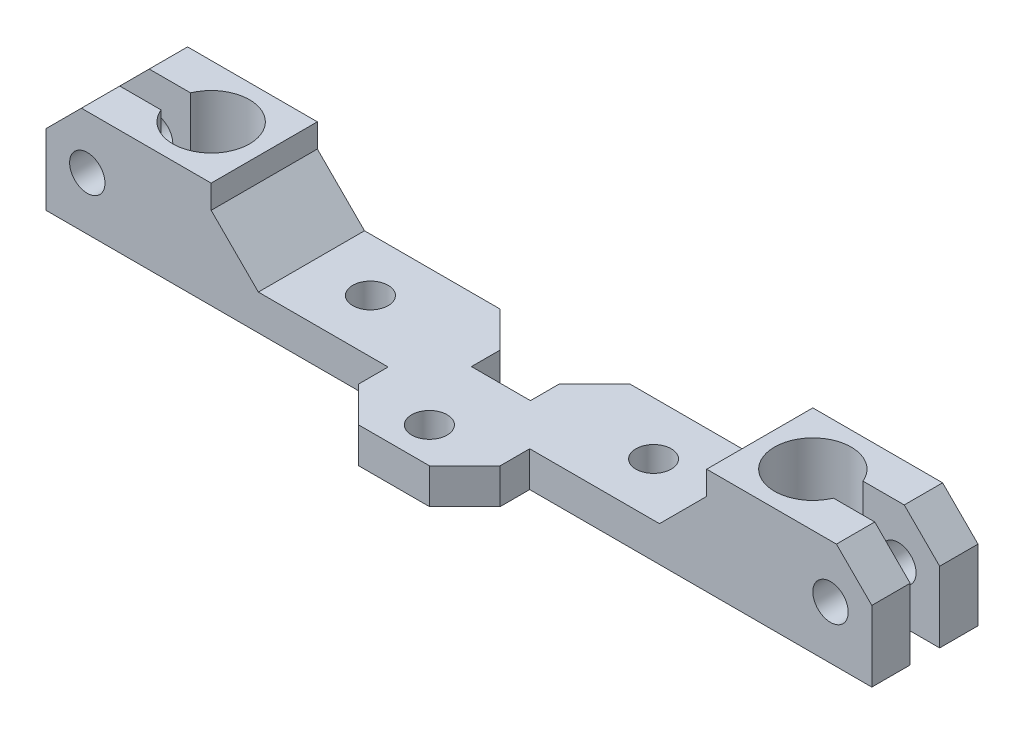
SolidWorks part; units mm, degrees
ref_plane "Plan de face" through (0, 0, 0) normal (0, 0, 1) x (1, 0, 0)
ref_plane "Plan de dessus" through (0, 0, 0) normal (0, 1, 0) x (1, 0, 0)
ref_plane "Plan de droite" through (0, 0, 0) normal (1, 0, 0) x (0, 0, -1)
sketch "Esquisse1" plane through (0, 0, 0) normal (0, 1, 0) x (1, 0, 0)
  line L0 (13.2163, 8.0498) -> (13.2163, -16.4268) construction
  line L1 (-21.7837, 7.99) -> (10.7163, 7.99)
  line L2 (-21.7837, 7.99) -> (-21.7837, -1.01)
  line L3 (-21.7837, -1.01) -> (7.2163, -1.01)
  line L4 (48.2163, 7.99) -> (48.2163, -1.01)
  line L5 (19.2163, -1.01) -> (48.2163, -1.01)
  line L6 (15.7163, 7.99) -> (48.2163, 7.99)
  line L7 (7.2163, -1.01) -> (7.2163, -6.51)
  line L8 (7.2163, -6.51) -> (19.2163, -6.51)
  line L9 (19.2163, -1.01) -> (19.2163, -6.51)
  line L11 (10.7163, 7.99) -> (10.7163, 2.5523)
  line L12 (10.7163, 2.5523) -> (15.7163, 2.5523)
  line L13 (15.7163, 7.99) -> (15.7163, 2.5523)
  dimension "D1" = 70
  dimension "D2" = 9
  dimension "D3" = 6
  dimension "D4" = 6
  dimension "D5" = 2.5
  dimension "D6" = 2.5
  dimension "D7" = 5.5
extrude "Boss.-Extru.1" add sketch "Esquisse1" along normal blind 3
sketch "Esquisse2" plane through (0, 3, 0) normal (0, 1, 0) x (1, 0, 0)
  line L1 (-21.7837, 7.99) -> (-7.7837, 7.99)
  line L2 (-21.7837, 7.99) -> (-21.7837, -1.01)
  line L3 (-21.7837, -1.01) -> (-7.7837, -1.01)
  line L4 (-7.7837, 7.99) -> (-7.7837, -1.01)
  line L5 (13.2163, 7.99) -> (13.2163, -21.6724) construction
  line L6 (48.2163, 7.99) -> (34.2163, 7.99)
  line L7 (48.2163, 7.99) -> (48.2163, -1.01)
  line L8 (48.2163, -1.01) -> (34.2163, -1.01)
  line L9 (34.2163, 7.99) -> (34.2163, -1.01)
  dimension "D1" = 21
  dimension "D2" = 21
extrude "Boss.-Extru.2" add sketch "Esquisse2" along normal blind 6
sketch "Esquisse3" plane through (0, 9, 0) normal (0, 1, 0) x (1, 0, 0)
  line L0 (-7.7837, -1.01) -> (-16.7837, 7.99) construction
  line L1 (-7.7837, 7.99) -> (-21.7837, 7.99) construction
  line L2 (34.2163, -1.01) -> (43.2163, 7.99) construction
  line L3 (48.2163, 7.99) -> (34.2163, 7.99) construction
  line L4 (34.2163, -1.01) -> (48.2163, -1.01) construction
  line L5 (-7.7837, -1.01) -> (-7.7837, 7.99) construction
  line L6 (34.2163, 7.99) -> (34.2163, -1.01) construction
  circle A0 centre (-12.2837, 3.49) radius 3.25
  circle A1 centre (38.7163, 3.49) radius 3.25
  dimension "D1" = 6.5
  dimension "D2" = 6.5
  dimension "D3" = 9
  dimension "D4" = 9
extrude "Enlèv. mat.-Extru.1" cut sketch "Esquisse3" against normal through all
chamfer "Chanfrein1" distance 4 angle 45 2 edges at (34.2163, 3, -3.49)
sketch "Esquisse4" plane through (0, 3, 0) normal (0, 1, 0) x (1, 0, 0)
  line L0 (-3.7837, 3.49) -> (30.2163, 3.49) construction
  line L1 (13.2163, 3.49) -> (13.2163, -6.51) construction
  line L2 (7.2163, -6.51) -> (19.2163, -6.51) construction
  line L3 (-3.7837, 7.99) -> (-3.7837, -1.01) construction
  line L4 (30.2163, -1.01) -> (30.2163, 7.99) construction
  circle A0 centre (1.2163, 3.49) radius 1.5
  circle A1 centre (25.2163, 3.49) radius 1.5
  circle A2 centre (13.2163, -3.51) radius 1.5
  dimension "D1" = 3
  dimension "D2" = 3
  dimension "D5" = 3
  dimension "D3" = 5
  dimension "D4" = 5
  dimension "D7" = 7
extrude "Enlèv. mat.-Extru.2" cut sketch "Esquisse4" against normal through all
sketch "Esquisse5" plane through (0, 9, 0) normal (0, 1, 0) x (1, 0, 0)
  line L0 (-21.7837, 3.49) -> (48.2163, 3.49) construction
  line L1 (-21.7837, 7.99) -> (-21.7837, -1.01) construction
  line L2 (48.2163, -1.01) -> (48.2163, 7.99) construction
  line L4 (-21.7837, 4.74) -> (-12.2837, 4.74)
  line L5 (-21.7837, 4.74) -> (-21.7837, 2.24)
  line L6 (-21.7837, 2.24) -> (-12.2837, 2.24)
  line L7 (-12.2837, 4.74) -> (-12.2837, 2.24)
  line L8 (48.2163, 4.74) -> (38.7163, 4.74)
  line L9 (48.2163, 4.74) -> (48.2163, 2.24)
  line L10 (48.2163, 2.24) -> (38.7163, 2.24)
  line L11 (38.7163, 4.74) -> (38.7163, 2.24)
  circle A0 centre (-12.2837, 3.49) radius 3.25 construction
  circle A1 centre (38.7163, 3.49) radius 3.25 construction
  dimension "D1" = 1.25
  dimension "D2" = 1.25
  dimension "D3" = 1.25
  dimension "D4" = 1.25
  dimension "D5" = 0
  dimension "D6" = 0
extrude "Enlèv. mat.-Extru.3" cut sketch "Esquisse5" against normal through all
sketch "Esquisse6" plane through (0, 0, 1.01) normal (0, 0, 1) x (1, 0, 0)
  line L0 (-21.7837, 9) -> (-14.7837, 0) construction
  line L1 (-21.7837, 0) -> (7.2163, 0) construction
  line L2 (-21.7837, 9) -> (-21.7837, 0) construction
  line L3 (48.2163, 9) -> (41.2163, 0) construction
  line L4 (48.2163, 9) -> (48.2163, 0) construction
  circle A0 centre (-18.2837, 4.5) radius 1.5
  circle A1 centre (44.7163, 4.5) radius 1.5
  dimension "D3" = 3
  dimension "D4" = 3
  dimension "D1" = 7
  dimension "D2" = 7
extrude "Enlèv. mat.-Extru.4" cut sketch "Esquisse6" against normal through all
chamfer "Chanfrein2" distance 3 angle 45 3 edges at (-21.7837, 9, -6.365) (48.2163, 9, -0.615) (48.2163, 9, -6.365)
chamfer "Chanfrein3" distance 3 angle 45 4 edges at (19.2163, 1.5, 6.51) (7.2163, 1.5, 6.51) (15.7163, 1.5, -7.99) (10.7163, 1.5, -7.99)
sketch "Esquisse7" plane through (0, 0, 0) normal (0, -1, 0) x (1, 0, 0)
  line L0 (35.4663, -3.49) -> (36.8323, -1.8858)
  line L1 (35.4663, -3.49) -> (36.8323, -5.0942)
  line L2 (41.7163, -2.24) -> (40.8517, -2.24)
  line L3 (41.7163, -4.74) -> (40.8517, -4.74)
  line L4 (13.2163, -2.5523) -> (13.2163, -9.6426) construction
  line L5 (15.7163, -2.5523) -> (10.7163, -2.5523) construction
  line L6 (-15.2837, -4.74) -> (-14.4192, -4.74)
  line L7 (-15.2837, -2.24) -> (-14.4192, -2.24)
  line L8 (-9.0337, -3.49) -> (-10.3998, -5.0942)
  line L9 (-9.0337, -3.49) -> (-10.3998, -1.8858)
  arc A0 (36.8323, -5.0942) -> (40.8517, -4.74) centre (38.7163, -3.49) ccw
  arc A1 (41.7163, -2.24) -> (41.7163, -4.74) centre (38.7163, -3.49) ccw construction
  arc A2 (41.7163, -2.24) -> (41.7163, -4.74) centre (38.7163, -3.49) ccw
  arc A3 (40.8517, -2.24) -> (36.8323, -1.8858) centre (38.7163, -3.49) ccw
  arc A4 (-14.4192, -2.24) -> (-10.3998, -1.8858) centre (-12.2837, -3.49) cw
  arc A5 (-15.2837, -2.24) -> (-15.2837, -4.74) centre (-12.2837, -3.49) cw
  arc A6 (-10.3998, -5.0942) -> (-14.4192, -4.74) centre (-12.2837, -3.49) cw
  arc M9 (41.7163, -4.74) -> (41.7163, -2.24) centre (38.7163, -3.49) cw
  arc M21 (-15.2837, -2.24) -> (-15.2837, -4.74) centre (-12.2837, -3.49) cw
extrude "Boss.-Extru.3" add sketch "Esquisse7" against normal blind 2 contours L7 A4 L9 M21 | L8 A6 L6 M21 | A3 L2 L0 M9 | A0 L1 L3 M9
